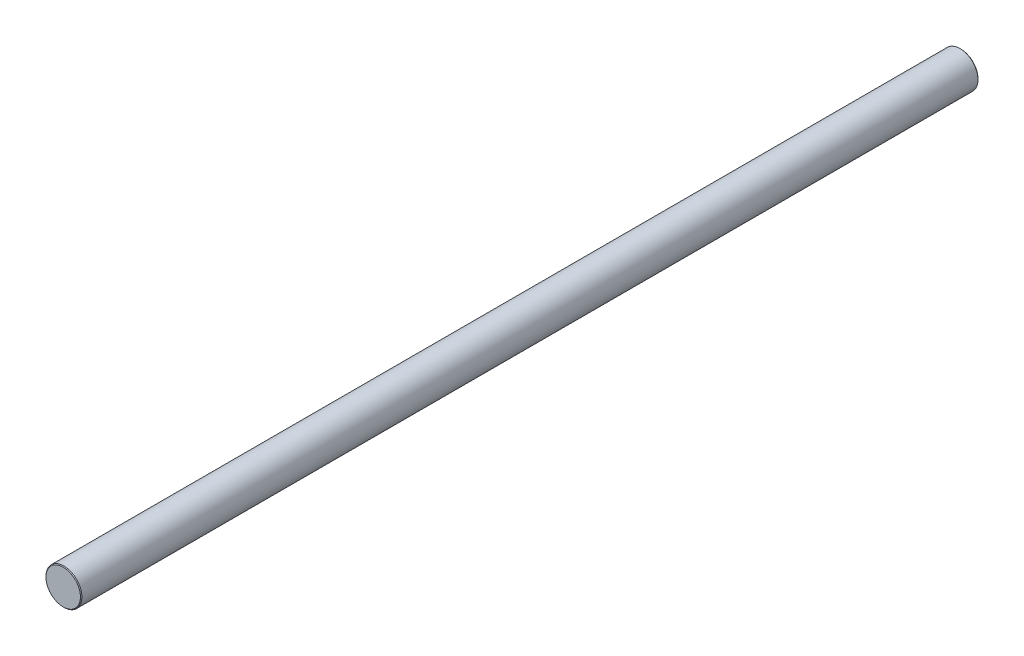
SolidWorks part; units mm, degrees
material "AISI 321 Gehärteter Edelstahl (SS)"
ref_plane "Ebene vorne" through (0, 0, 0) normal (0, 0, 1) x (1, 0, 0)
ref_plane "Ebene oben" through (0, 0, 0) normal (0, 1, 0) x (1, 0, 0)
ref_plane "Ebene rechts" through (0, 0, 0) normal (1, 0, 0) x (0, 0, -1)
sketch "Skizze1" plane through (0, 0, 0) normal (0, 0, 1) x (1, 0, 0)
  circle A0 centre (0, 0) radius 5
  dimension "D1" = 10
extrude "Aufsatz-Linear austragen1" add sketch "Skizze1" along normal blind 250
chamfer "Fase1" distance 0.2 angle 45 2 edges at (5, 0, 250) (5, 0, 0)
